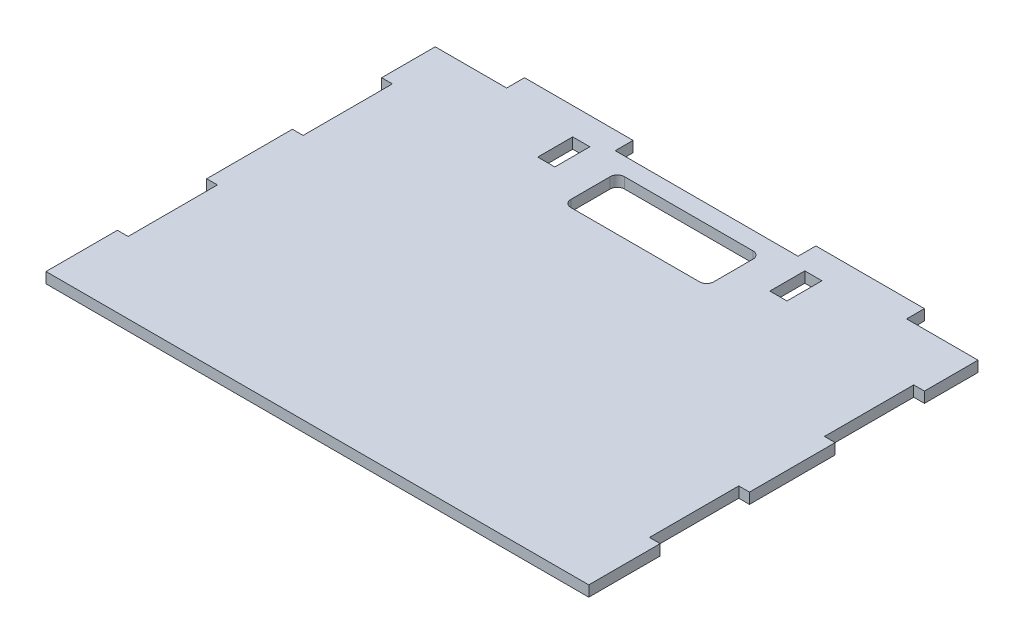
SolidWorks part; units mm, degrees
ref_plane "Front Plane" through (0, 0, 0) normal (0, 0, 1) x (1, 0, 0)
ref_plane "Top Plane" through (0, 0, 0) normal (0, 1, 0) x (1, 0, 0)
ref_plane "Right Plane" through (0, 0, 0) normal (1, 0, 0) x (0, 0, -1)
sketch "Sketch1" plane through (0, 0, 0) normal (0, 1, 0) x (1, 0, 0)
  line L0 (76, -57) -> (0, -57) construction
  line L2 (-76, -57) -> (-76, 57) construction
  line L3 (-76, 57) -> (76, 57) construction
  line L4 (76, -57) -> (76, 57) construction
  line L5 (0, 52) -> (0, -57)
  line L6 (-76, 0) -> (76, 0) construction
  line L7 (0, -57) -> (-76, -57)
  line L8 (-76, -57) -> (-76, -37)
  line L9 (-76, -37) -> (-73, -37)
  line L10 (-73, -37) -> (-73, -12)
  line L11 (-73, -12) -> (-76, -12)
  line L13 (-76, 52) -> (-56, 52)
  line L14 (-56, 52) -> (-56, 57)
  line L15 (-56, 57) -> (-25.6, 57)
  line L16 (-25.6, 57) -> (-25.6, 52)
  line L17 (-25.6, 52) -> (0, 52)
  line L18 (0, 52) -> (0, 57) construction
  line L19 (-76, -12) -> (-76, 12)
  line L20 (-76, 12) -> (-73, 12)
  line L21 (-73, 12) -> (-73, 37)
  line L22 (-73, 37) -> (-76, 37)
  line L23 (-76, 37) -> (-76, 52)
  point P76 (0, 0)
  dimension "D1" = 114
  dimension "D2" = 152
  dimension "D3" = 3
  dimension "D4" = 20
  dimension "D5" = 5
  dimension "D6" = 20
  dimension "D7" = 30.4
  dimension "D8" = 25
  dimension "D9" = 20
extrude "Boss-Extrude1" add sketch "Sketch1" along normal blind 3
mirror "Mirror1" about plane through (0, 3, -52) normal (-1, 0, 0) of "Boss-Extrude1"
sketch "Sketch2" plane through (0, 3, 0) normal (0, 1, 0) x (1, 0, 0)
  line L0 (0, 0) -> (0, 52) construction
  line L1 (-34.9, 49.4) -> (-30.1, 49.4)
  line L2 (-34.9, 49.4) -> (-34.9, 39.6)
  line L3 (-34.9, 39.6) -> (-30.1, 39.6)
  line L4 (-30.1, 49.4) -> (-30.1, 39.6)
  line L5 (-32.5, 39.6) -> (-32.5, 49.4) construction
  line L6 (-34.9, 44.5) -> (-30.1, 44.5) construction
  line L7 (30.1, 49.4) -> (34.9, 49.4)
  line L8 (30.1, 49.4) -> (30.1, 39.6)
  line L9 (30.1, 39.6) -> (34.9, 39.6)
  line L10 (34.9, 49.4) -> (34.9, 39.6)
  line L11 (32.5, 39.6) -> (32.5, 49.4) construction
  line L12 (30.1, 44.5) -> (34.9, 44.5) construction
  line L13 (25.6, 52) -> (-25.6, 52) construction
  line L15 (-18, 47) -> (18, 47)
  line L16 (-20, 45) -> (-20, 34)
  line L17 (-18, 32) -> (18, 32)
  line L18 (20, 45) -> (20, 34)
  arc A0 (18, 47) -> (20, 45) centre (18, 45) cw
  arc A1 (18, 32) -> (20, 34) centre (18, 34) ccw
  arc A2 (-20, 34) -> (-18, 32) centre (-18, 34) ccw
  arc A3 (-18, 47) -> (-20, 45) centre (-18, 45) ccw
  point P164 (-32.5, 44.5)
  point P253 (32.5, 44.5)
  dimension "D6" = 2
  dimension "D1" = 4.8
  dimension "D2" = 4.8
  dimension "D3" = 9.8
  dimension "D7" = 5
  dimension "D8" = 40
  dimension "D9" = 15
  dimension "D5" = 32.5
  dimension "D4" = 7.5
extrude "Cut-Extrude1" cut sketch "Sketch2" against normal through all
equation "\"3mm akryyli\"= 3mm"
equation "\"5mm akryyli\"= 5mm"
equation "\"D3@Sketch1\"=\"3mm akryyli\""
equation "\"D5@Sketch1\"=\"5mm akryyli\""
equation "\"D1@Boss-Extrude1\"=\"3mm akryyli\""
equation "\"D1@Sketch2\"=\"5mm akryyli\"-0.2"
equation "\"D2@Sketch2\"=\"5mm akryyli\"-0.2"
